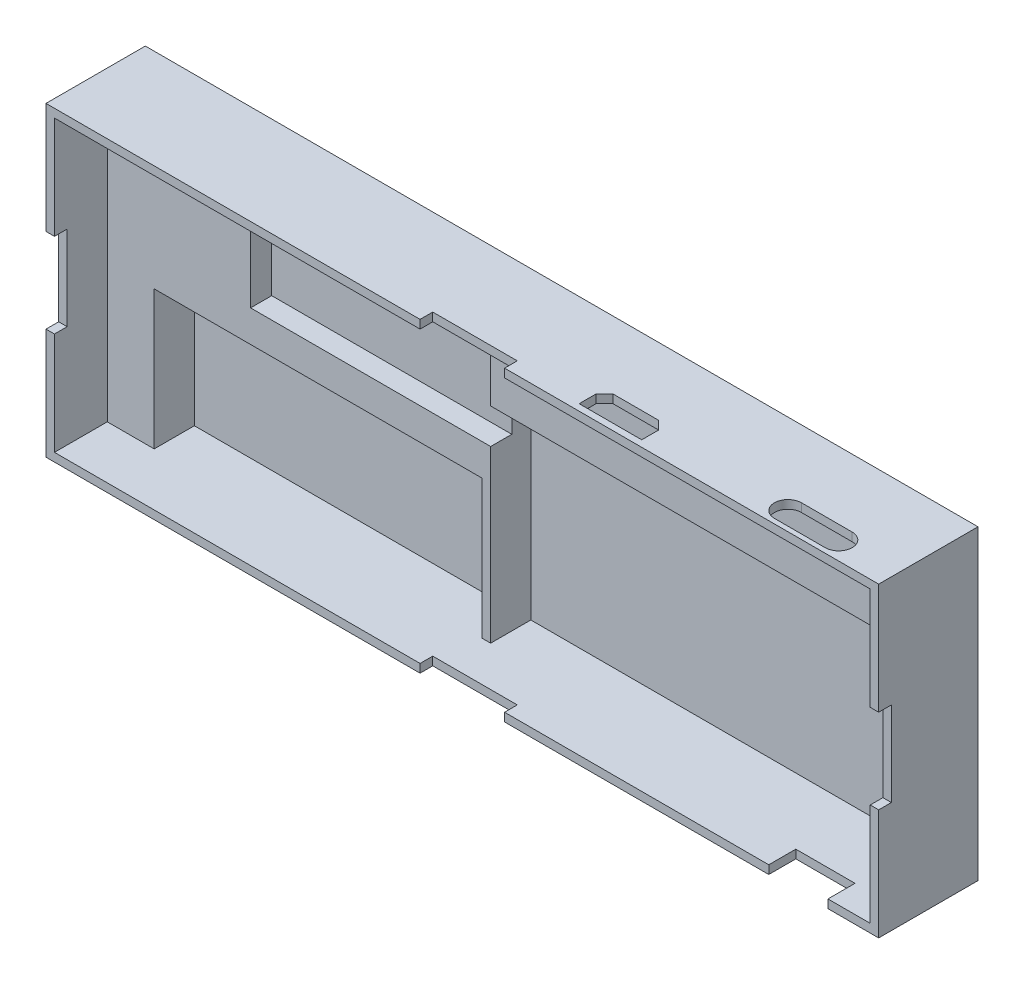
SolidWorks part; units mm, degrees
ref_plane "Alzado" through (0, 0, 0) normal (0, 0, 1) x (1, 0, 0)
ref_plane "Planta" through (0, 0, 0) normal (0, 1, 0) x (1, 0, 0)
ref_plane "Vista lateral" through (0, 0, 0) normal (1, 0, 0) x (0, 0, -1)
sketch "Croquis1" plane through (0, 0, 0) normal (0, 0, 1) x (1, 0, 0)
  line L1 (-51.0756, 27.071) -> (45.4244, 27.071)
  line L2 (-51.0756, 27.071) -> (-51.0756, -7.179)
  line L3 (-51.0756, -7.179) -> (45.4244, -7.179)
  line L4 (45.4244, 27.071) -> (45.4244, -7.179)
  dimension "D1" = 96.5
  dimension "D2" = 34.25
extrude "Saliente-Extruir1" add sketch "Croquis1" along normal blind 0.75
sketch "Croquis3" plane through (0, 0, 0) normal (0, 0, -1) x (-1, 0, 0)
  line L1 (-45.4244, 27.071) -> (51.0756, 27.071)
  line L2 (-45.4244, 27.071) -> (-45.4244, -7.179)
  line L3 (-45.4244, -7.179) -> (51.0756, -7.179)
  line L4 (51.0756, 27.071) -> (51.0756, -7.179)
  line L5 (52.0756, -8.179) -> (-46.4244, -8.179)
  line L6 (52.0756, -8.179) -> (52.0756, 28.071)
  line L7 (52.0756, 28.071) -> (-46.4244, 28.071)
  line L8 (-46.4244, -8.179) -> (-46.4244, 28.071)
  dimension "D1" = 1
  dimension "D2" = 1
  dimension "D3" = 1
  dimension "D4" = 1
extrude "Saliente-Extruir2" add sketch "Croquis3" against normal blind 11.75
sketch "Croquis5" plane through (0, 0, 0.75) normal (0, 0, 1) x (1, 0, 0)
  line L0 (-5.7256, -7.179) -> (-5.7256, 17.121)
  line L1 (45.4244, -7.179) -> (-51.0756, -7.179) construction
  line L2 (-5.7256, 17.121) -> (45.4244, 17.121)
  line L3 (45.4244, 27.071) -> (45.4244, -7.179) construction
  line L4 (-5.7256, -7.179) -> (-6.7256, -7.179)
  line L5 (-6.7256, -7.179) -> (-6.7256, 27.071)
  line L6 (-6.7256, 27.071) -> (45.4244, 27.071)
  line L7 (45.4244, 27.071) -> (45.4244, 17.121)
  line L8 (45.4244, 27.071) -> (-51.0756, 27.071) construction
  dimension "D1" = 24.3
  dimension "D2" = 51.15
  dimension "D3" = 0
  dimension "D4" = 1
extrude "Saliente-Extruir3" add sketch "Croquis5" along normal blind 4.75
sketch "Croquis6" plane through (0, 0, 0) normal (0, 0, 1) x (1, 0, 0)
  line L0 (-6.7256, 9.221) -> (-6.7256, 27.071)
  line L3 (-6.7256, 9.221) -> (-45.5256, 9.221)
  line L4 (-45.5256, -7.179) -> (-45.5256, 9.221)
  line L6 (-6.7256, 27.071) -> (-51.0756, 27.071)
  line L7 (-51.0756, 27.071) -> (-51.0756, -7.179)
  line L8 (-51.0756, -7.179) -> (-45.5256, -7.179)
  dimension "D1" = 38.8
  dimension "D2" = 16.4
extrude "Saliente-Extruir4" add sketch "Croquis6" along normal blind 3
sketch "Croquis7" plane through (0, 0, 3) normal (0, 0, 1) x (1, 0, 0)
  line L0 (-34.1256, 27.071) -> (-51.0756, 27.071)
  line L3 (-6.7256, 12.971) -> (-34.1256, 12.971)
  line L4 (-34.1256, 27.071) -> (-34.1256, 12.971)
  line L5 (-6.7256, 27.071) -> (-51.0756, 27.071) construction
  line L6 (-51.0756, 27.071) -> (-51.0756, -7.179)
  line L7 (-51.0756, -7.179) -> (-45.5256, -7.179) construction
  line L8 (-51.0756, 27.071) -> (-51.0756, -7.179) construction
  line L9 (-51.0756, -7.179) -> (-45.5256, -7.179)
  line L10 (-45.5256, -7.179) -> (-45.5256, 9.221)
  line L11 (-45.5256, 9.221) -> (-6.7256, 9.221)
  line L12 (-45.5256, 9.221) -> (-6.7256, 9.221) construction
  line L13 (-6.7256, 9.221) -> (-6.7256, 12.971)
  dimension "D1" = 14.1
extrude "Saliente-Extruir5" add sketch "Croquis7" along normal blind 2.5
sketch "Croquis8" plane through (0, 0, 5.5) normal (0, 0, 1) x (1, 0, 0)
  line L0 (45.4244, 27.071) -> (-6.7256, 27.071) construction
  line L1 (-6.7256, 12.971) -> (-5.7256, 12.971)
  line L2 (-6.7256, 12.971) -> (-6.7256, 27.071)
  line L3 (-6.7256, 27.071) -> (-5.7256, 27.071)
  line L4 (-5.7256, 12.971) -> (-5.7256, 27.071)
extrude "Cortar-Extruir1" cut sketch "Croquis8" against normal up to surface (2.5 mm away) up to face at (-20.4256, 20.021, 3)
sketch "Croquis9" plane through (0, 27.071, 0) normal (0, -1, 0) x (1, 0, 0)
  line L1 (10.2244, 10.98) -> (17.6244, 10.98)
  line L2 (10.2244, 10.98) -> (10.2244, 8.98)
  line L3 (11.2244, 7.98) -> (16.6244, 7.98)
  line L4 (17.6244, 10.98) -> (17.6244, 8.98)
  line L5 (33.5244, 11.18) -> (39.5244, 11.18)
  line L7 (33.5244, 7.98) -> (39.5244, 7.98)
  line L9 (45.4244, 5.5) -> (-5.7256, 5.5) construction
  line L10 (10.2244, 8.98) -> (11.2244, 7.98)
  line L11 (16.6244, 7.98) -> (17.6244, 8.98)
  arc A0 (33.5244, 11.18) -> (33.5244, 7.98) centre (33.5244, 9.58) ccw
  arc A1 (39.5244, 7.98) -> (39.5244, 11.18) centre (39.5244, 9.58) ccw
  dimension "D3" = 2.48
  dimension "D5" = 2.48
  dimension "D7" = 7.4
extrude "Cortar-Extruir2" cut sketch "Croquis9" against normal blind 2.5
sketch "Croquis10" plane through (0, 0, 11.75) normal (0, 0, 1) x (1, 0, 0)
  line L0 (-52.0756, 28.071) -> (46.4244, 28.071) construction
  line L1 (-7.8256, 36.2209) -> (2.1744, 36.2209)
  line L2 (-7.8256, 36.2209) -> (-7.8256, 14.946)
  line L3 (-7.8256, -27.1591) -> (2.1744, -27.1591)
  line L4 (2.1744, 36.2209) -> (2.1744, 14.946)
  line L5 (-73.5039, 14.946) -> (-7.8256, 14.946)
  line L6 (-73.5039, 14.946) -> (-73.5039, 4.946)
  line L7 (-73.5039, 4.946) -> (-7.8256, 4.946)
  line L8 (54.7599, 14.946) -> (54.7599, 4.946)
  line L9 (46.4244, 28.071) -> (46.4244, -8.179) construction
  line L10 (2.1744, 4.946) -> (2.1744, -27.1591)
  line L11 (-7.8256, 4.946) -> (-7.8256, -27.1591)
  line L12 (2.1744, 14.946) -> (54.7599, 14.946)
  line L13 (2.1744, 4.946) -> (54.7599, 4.946)
  point P10 (-2.8256, 36.2209)
  point P11 (-2.8256, 28.071)
  point P12 (54.7599, 9.946)
  point P15 (46.4244, 9.946)
  dimension "D1" = 0
  dimension "D2" = 0
  dimension "D3" = 10
  dimension "D4" = 10
extrude "Cortar-Extruir3" cut sketch "Croquis10" against normal blind 1.5
sketch "Croquis11" plane through (0, -8.179, 0) normal (0, -1, 0) x (1, 0, 0)
  line L0 (46.4244, 11.75) -> (2.1744, 11.75) construction
  line L1 (33.4244, 11.75) -> (40.4244, 11.75)
  line L2 (33.4244, 11.75) -> (33.4244, 8.55)
  line L3 (33.4244, 8.55) -> (40.4244, 8.55)
  line L4 (40.4244, 11.75) -> (40.4244, 8.55)
  line L5 (46.4244, 11.75) -> (46.4244, 0) construction
  dimension "D1" = 6
  dimension "D2" = 13
  dimension "D3" = 3.2
extrude "Cortar-Extruir4" cut sketch "Croquis11" against normal blind 10
